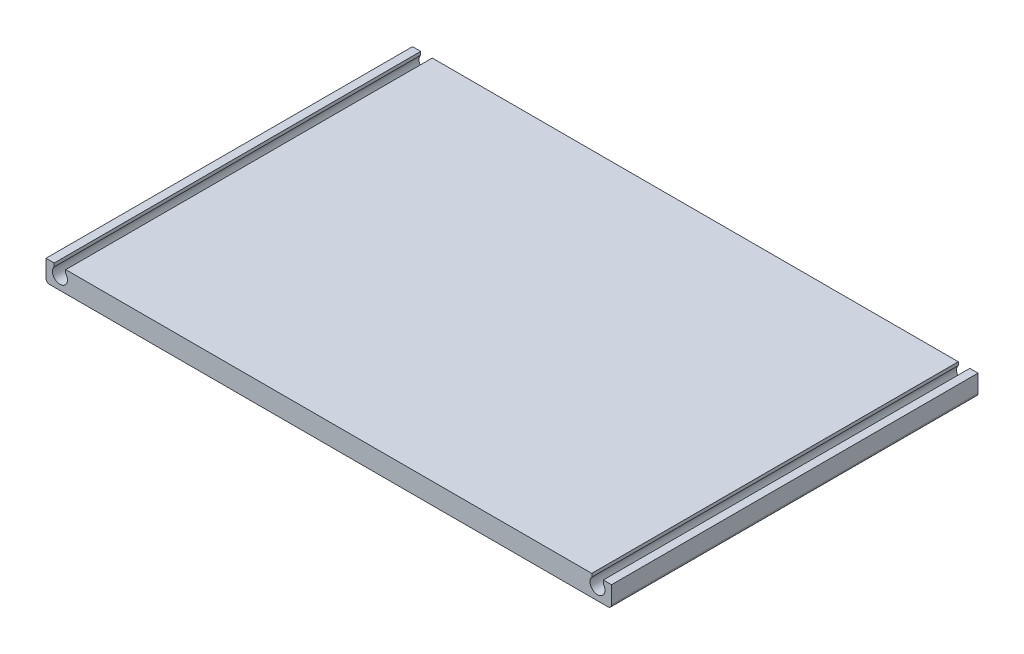
SolidWorks part; units mm, degrees
ref_plane "前基準面" through (0, 0, 0) normal (0, 0, 1) x (1, 0, 0)
ref_plane "上基準面" through (0, 0, 0) normal (0, 1, 0) x (1, 0, 0)
ref_plane "右基準面" through (0, 0, 0) normal (1, 0, 0) x (0, 0, -1)
sketch "草圖1" plane through (0, 0, 0) normal (0, 1, 0) x (1, 0, 0)
  line L1 (81, -52.5) -> (-81, -52.5)
  line L2 (81, -52.5) -> (81, 52.5)
  line L3 (81, 52.5) -> (-81, 52.5)
  line L4 (-81, -52.5) -> (-81, 52.5)
  line L5 (81, -52.5) -> (-81, 52.5) construction
  line L6 (81, 52.5) -> (-81, -52.5) construction
  point P0 (0, 0)
  dimension "D1" = 105
  dimension "D2" = 162
extrude "填料-伸長1" add sketch "草圖1" along normal blind 6
sketch "草圖3" plane through (0, 0, 52.5) normal (0, 0, 1) x (1, 0, 0)
  line L0 (75.5, 5) -> (75.5, 6)
  line L1 (-81, 6) -> (81, 6) construction
  line L2 (75.5, 6) -> (78.5, 6)
  line L3 (78.5, 6) -> (78.5, 5)
  line L4 (81, 6) -> (81, 0) construction
  line L5 (0, 0) -> (0, 33.4561) construction
  arc A0 (75.5, 5) -> (78.5, 5) centre (77, 3.6771) ccw
  dimension "D1" = 2
  dimension "D2" = 1
  dimension "D3" = 4
  dimension "D4" = 3
  dimension "D5" = 154
extrude "除料-伸長1" cut sketch "草圖3" against normal through all
mirror "鏡射1" about plane through (0, 0, 0) normal (1, 0, 0) of "除料-伸長1"
fillet "圓角1" radius 1 2 edges at (-81, 0, 0) (81, 0, 0)
sketch "草圖4" plane through (0, 0, -52.5) normal (0, 0, -1) x (-1, 0, 0)
  line L1 (10, 0) -> (-10, 0)
  line L2 (10, 0) -> (10, -14.5)
  line L3 (10, -14.5) -> (-10, -14.5)
  line L4 (-10, 0) -> (-10, -14.5)
  line L5 (10, 0) -> (-10, -14.5) construction
  line L6 (10, -14.5) -> (-10, 0) construction
  line L7 (-80, 0) -> (80, 0) construction
  point P0 (0, -7.25)
  dimension "D1" = 14.5
  dimension "D2" = 20
extrude "填料-伸長2" add sketch "草圖4" against normal blind 5 from offset 20 offset against normal yes
hole_wizard "Ø4.0mm 定位孔1" positions "草圖5" profile "草圖6" hole size "Ø4.0" standard "ISO" end condition through all
sketch "草圖5" plane through (0, 0, -32.5) normal (0, 0, -1) x (-1, 0, 0)
  line L0 (-10, -8) -> (10, -8) construction
  line L1 (-10, 0) -> (-10, -14.5) construction
  line L2 (10, -14.5) -> (10, 0) construction
  line L3 (0, -8) -> (0, 6) construction
  line L5 (-10, 6) -> (10, 6) construction
  line L11 (-10, -14.5) -> (10, -14.5) construction
  point P7 (-5, -8)
  point P9 (5, -8)
  dimension "D1" = 10
  dimension "D2" = 6.5
  dimension "D3" = 6.5
sketch "草圖6" plane through (-5, -8, -32.5) normal (1, 0, 0) x (0, 1, 0)
  line L0 (0, 0) -> (0, 85)
  line L1 (0, 85) -> (2, 85)
  line L2 (2, 85) -> (2, 0.025)
  line L3 (2, 0.025) -> (2.025, 0)
  line L5 (2.025, 0) -> (0, 0)
  line L6 (-2, 0.025) -> (-2.025, 0) construction
  line L11 (0, -6.35) -> (0, 107.95) construction
  dimension "砮 ふ 畖" = 4
  dimension "砮 ふ瞏 " = 85
  dimension " 狠繞ふ 畖" = 4.05
  dimension " 狠繞ふà " = 90
sketch "草圖7" plane through (0, 0, -27.5) normal (0, 0, 1) x (1, 0, 0)
  line L0 (-10, 0) -> (10, 0) construction
  line L1 (22.75, 0) -> (16.75, 0)
  line L2 (22.75, 0) -> (22.75, -9)
  line L3 (22.75, -9) -> (16.75, -9)
  line L4 (-22.75, 0) -> (-22.75, -9)
  line L6 (16.75, -9) -> (-16.75, -9) construction
  line L7 (-16.75, -9) -> (16.75, -9) construction
  line L8 (-16.75, -9) -> (-16.75, 0)
  line L9 (-16.75, 0) -> (16.75, 0) construction
  line L10 (16.75, -9) -> (16.75, 0)
  line L11 (-16.75, -9) -> (-22.75, -9)
  line L12 (16.75, 0) -> (-16.75, 0) construction
  line L13 (-16.75, 0) -> (-22.75, 0)
  point P6 (0, 0)
  dimension "D1" = 9
  dimension "D2" = 45.5
  dimension "D3" = 6
extrude "填料-伸長3" add sketch "草圖7" along normal blind 20.5 from offset 15
sketch "草圖8" plane through (0, 0, 8) normal (0, 0, 1) x (1, 0, 0)
  line L0 (16.75, -9) -> (22.75, -9) construction
  line L1 (-22.75, -9) -> (-16.75, -9) construction
  circle A0 centre (-19.75, -6) radius 1.5
  circle A1 centre (19.75, -6) radius 1.5
  point P6 (19.75, -9)
  point P10 (-19.75, -9)
  dimension "D1" = 4.482
  dimension "3" = 3
extrude "除料-伸長2" cut sketch "草圖8" against normal through all
sketch "草圖9" plane through (0, 0, 52.5) normal (0, 0, 1) x (1, 0, 0)
  line L4 (-78.65, 6) -> (-75.35, 6)
  line L5 (0, -11.275) -> (0, 11.275) construction
  line L6 (-75.35, 6) -> (-75.35, 5.0555)
  line L7 (-78.65, 5.0555) -> (-78.65, 6)
  line L8 (-75.35, 6) -> (-75.35, 5.0555)
  line L9 (-78.65, 5.0555) -> (-78.65, 6)
  line L10 (78.65, 5.0555) -> (78.65, 6)
  line L11 (75.35, 6) -> (75.35, 5.0555)
  line L12 (78.65, 6) -> (75.35, 6)
  arc A2 (78.65, 5.0555) -> (75.35, 5.0555) centre (77, 3.6771) cw
  arc A3 (-78.65, 5.0555) -> (-75.35, 5.0555) centre (-77, 3.6771) ccw
  arc A4 (-78.65, 5.0555) -> (-75.35, 5.0555) centre (-77, 3.6771) ccw
  dimension "D1" = 0.15
extrude "除料-伸長3" cut sketch "草圖9" against normal through all
sketch "草圖10" plane through (0, 0, -32.5) normal (0, 0, -1) x (-1, 0, 0)
  line L4 (-10, 0) -> (-10, -14.5)
  line L5 (-10, -14.5) -> (10, -14.5)
  line L6 (10, -14.5) -> (10, 0)
  line L7 (10, 0) -> (-10, 0)
  line L12 (-10, 0) -> (-10, -14.5)
  line L13 (-10, -14.5) -> (10, -14.5)
  line L14 (10, -14.5) -> (10, 0)
  line L15 (10, 0) -> (-10, 0)
  line L16 (40, 0) -> (40, -14.5)
  line L17 (40, -14.5) -> (60, -14.5)
  line L18 (60, -14.5) -> (60, 0)
  line L19 (60, 0) -> (40, 0)
  line L20 (-10, 0) -> (40, 0) construction
  circle A0 centre (55, -8) radius 2.025
  circle A1 centre (45, -8) radius 2
  circle A4 centre (5, -8) radius 2.025
  circle A5 centre (-5, -8) radius 2
  circle A8 centre (-5, -8) radius 2 construction
  circle A9 centre (5, -8) radius 2.025 construction
  dimension "D3" = 50
  dimension "D1" = 0
  dimension "D2" = 2
extrude "填料-伸長4" add sketch "草圖10" against normal up to surface (5 mm away) up to face at (7, -8, -27.5)
sketch "草圖11" [suppressed] plane through (0, 0, -32.5) normal (0, 0, 1) x (1, 0, 0)
  line L0 (40, 0) -> (40, -14.5)
  line L1 (40, -14.5) -> (60, -14.5)
  line L2 (60, -14.5) -> (60, 0)
  line L3 (60, 0) -> (40, 0)
  line L4 (-10, -14.5) -> (-10, 0) construction
  line L5 (10, -14.5) -> (-10, -14.5) construction
  line L12 (-10, 0) -> (-10, -14.5)
  line L13 (-10, -14.5) -> (10, -14.5)
  line L14 (10, -14.5) -> (10, 0)
  line L15 (10, 0) -> (-10, 0)
  line L16 (-10, 0) -> (40, 0) construction
  circle A0 centre (5, -8) radius 2 construction
  circle A1 centre (-5, -8) radius 2 construction
  circle A4 centre (5, -8) radius 2
  circle A5 centre (-5, -8) radius 2
  circle A6 centre (55, -8) radius 2
  circle A7 centre (45, -8) radius 2
  dimension "D3" = 50
  dimension "D1" = 0
  dimension "D2" = 2
extrude "填料-伸長5" [suppressed] add sketch "草圖11" along normal up to surface (5 mm away)
sketch "草圖12" plane through (0, 0, 52.5) normal (0, 0, 1) x (1, 0, 0)
  circle A2 centre (-45, -8) radius 2.1
  circle A3 centre (-45, -8) radius 2.1
  circle A5 centre (-55, -8) radius 2.125
  circle A6 centre (-55, -8) radius 2.125
  circle A24 centre (-19.75, -6) radius 1.6
  circle A25 centre (-19.75, -6) radius 1.6
  circle A27 centre (-5, -8) radius 2.1
  circle A28 centre (-5, -8) radius 2.1
  circle A30 centre (5, -8) radius 2.1
  circle A31 centre (5, -8) radius 2.1
  circle A33 centre (19.75, -6) radius 1.6
  circle A34 centre (19.75, -6) radius 1.6
  dimension "D1" = 0.1
  dimension "D2" = 0.1
  dimension "D3" = 0.1
  dimension "D4" = 0.1
  dimension "D5" = 0.1
  dimension "D6" = 0.1
extrude "除料-伸長4" cut sketch "草圖12" against normal through all
sketch "草圖13" [suppressed] plane through (0, 0, -27.5) normal (0, 0, 1) x (1, 0, 0)
  circle A2 centre (45, -8) radius 2.1
  circle A3 centre (45, -8) radius 2.1
  circle A4 centre (19.75, -6) radius 1.6
  circle A5 centre (55, -8) radius 2.1
  circle A6 centre (55, -8) radius 2.1
  circle A7 centre (19.75, -6) radius 1.6
  circle A9 centre (5, -8) radius 2.1
  circle A10 centre (5, -8) radius 2.1
  circle A12 centre (-5, -8) radius 2.1
  circle A13 centre (-5, -8) radius 2.1
  circle A15 centre (-19.75, -6) radius 1.6
  circle A16 centre (-19.75, -6) radius 1.6
  dimension "D1" = 0.1
  dimension "D2" = 0.1
  dimension "D3" = 0.1
  dimension "D4" = 0.1
  dimension "D5" = 0.1
  dimension "D6" = 0.1
extrude "除料-伸長5" [suppressed] cut sketch "草圖13" against normal through all
